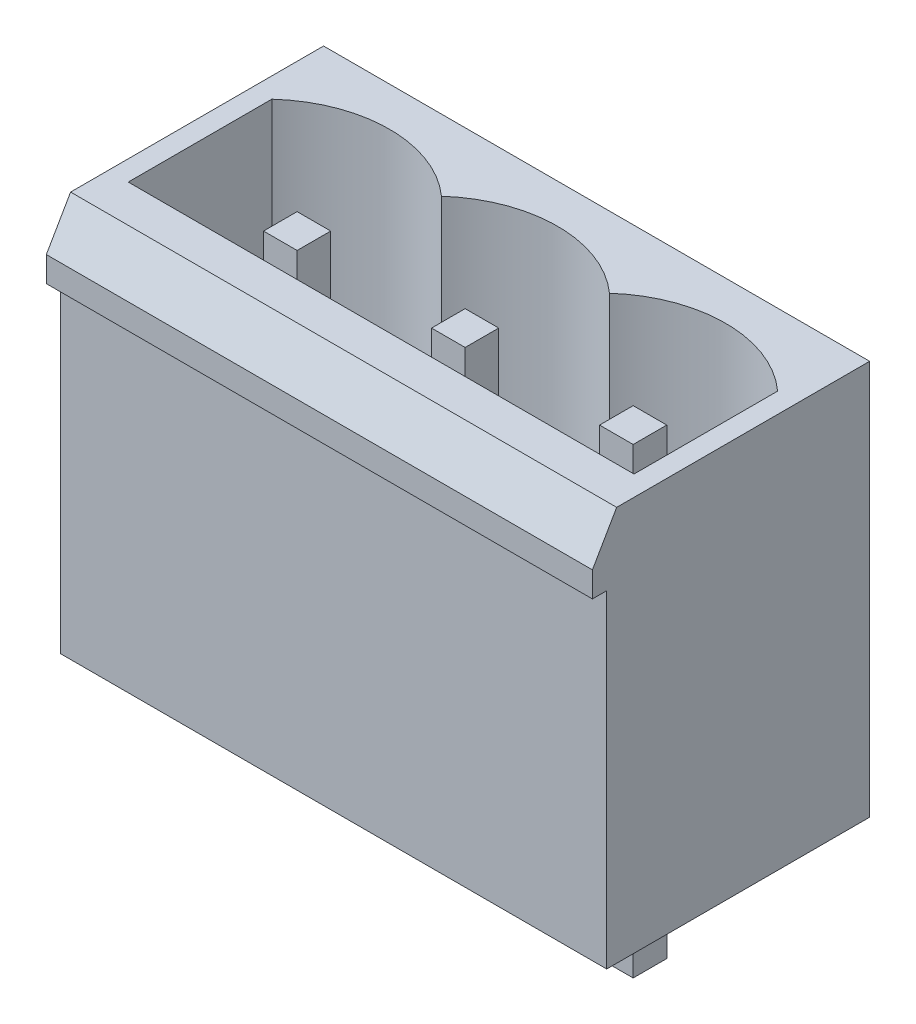
SolidWorks part; units mm, degrees
ref_plane "front" through (0, 0, 0) normal (0, 0, 1) x (1, 0, 0)
ref_plane "top" through (0, 0, 0) normal (0, 1, 0) x (1, 0, 0)
ref_plane "right" through (0, 0, 0) normal (1, 0, 0) x (0, 0, -1)
ref_plane "Plane1" through (3.175, 0, 0) normal (1, 0, 0) x (0, 0, -1)
sketch "Sketch1" plane through (3.175, 0, 0) normal (1, 0, 0) x (0, 0, -1)
  line L0 (-3.9751, 0) -> (-3.9751, 9.906)
  line L1 (-3.9751, 9.906) -> (-4.4069, 9.906)
  line L2 (-4.4069, 9.906) -> (-4.4069, 10.668)
  line L3 (-4.4069, 10.668) -> (-3.6737, 11.938)
  line L4 (-3.6737, 11.938) -> (3.9751, 11.938)
  line L5 (3.9751, 11.938) -> (3.9751, 0)
  line L6 (3.9751, 0) -> (-3.9751, 0)
  dimension "D1" = 7.9502
  dimension "D2" = 8.382
  dimension "D3" = 0.762
  dimension "D4" = 2.032
  dimension "D5" = 60
  dimension "D6" = 11.938
extrude "Extrude1" add sketch "Sketch1" against normal blind 16.51
sketch "Sketch3" plane through (0, 11.938, 0) normal (0, 1, 0) x (1, 0, 0)
  line L0 (-2.5654, 1.8009) -> (-2.5654, -2.54)
  line L1 (-2.5654, -2.54) -> (2.5654, -2.54)
  line L2 (2.5654, -2.54) -> (2.5654, 1.8009)
  arc A0 (2.5654, 1.8009) -> (-2.5654, 1.8009) centre (0, -1.016) ccw
  point P0 (0, 2.794)
  point P6 (0, -2.54)
  dimension "D3" = 3.81
  dimension "D1" = 5.1308
  dimension "D2" = 2.54
  dimension "D4" = 2.794
extrude "Cut-Extrude1" cut sketch "Sketch3" against normal blind 10.16
sketch "Sketch2" plane through (0, 0, 0) normal (0, 1, 0) x (1, 0, 0)
  line L1 (-0.508, 0.508) -> (0.508, 0.508)
  line L2 (-0.508, 0.508) -> (-0.508, -0.508)
  line L3 (-0.508, -0.508) -> (0.508, -0.508)
  line L4 (0.508, 0.508) -> (0.508, -0.508)
  point P4 (0.508, 0)
  point P5 (0, -0.508)
  dimension "D1" = 1.016
extrude "Extrude2" add sketch "Sketch2" against normal blind 3.302 and the other way blind 10.668
pattern_linear "LPattern1" count 3 spacing 5.08 along (-1, 0, 0) of "Cut-Extrude1", "Extrude2"
